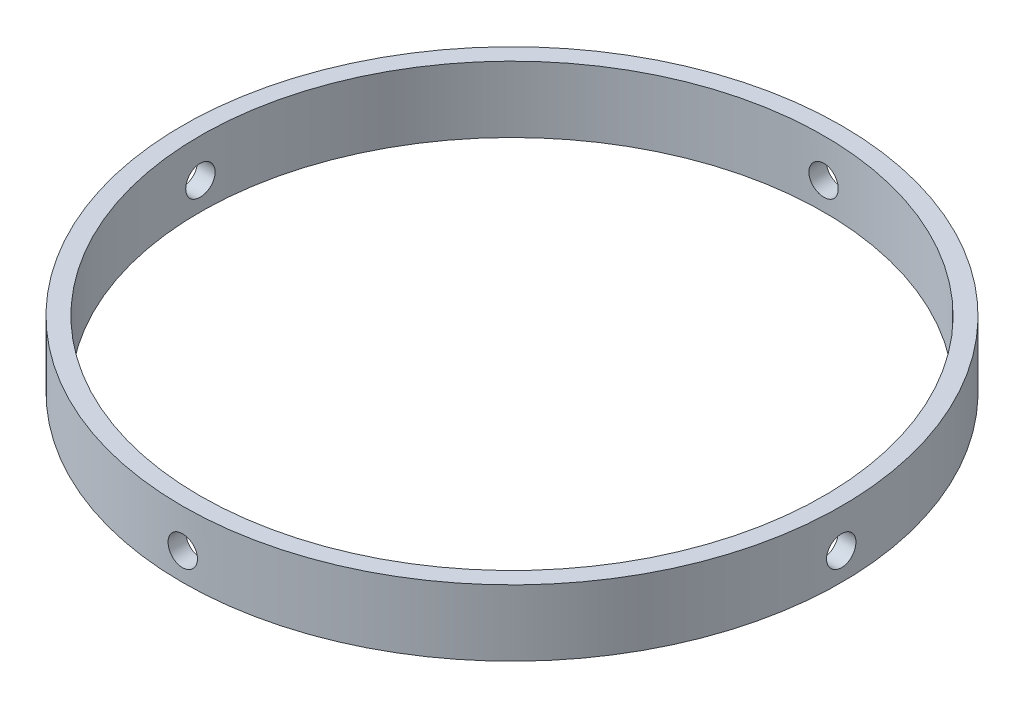
SolidWorks part; units mm, degrees
ref_plane "Front Plane" through (0, 0, 0) normal (0, 0, 1) x (1, 0, 0)
ref_plane "Top Plane" through (0, 0, 0) normal (0, 1, 0) x (1, 0, 0)
ref_plane "Right Plane" through (0, 0, 0) normal (1, 0, 0) x (0, 0, -1)
sketch "Sketch1" plane through (0, 0, 0) normal (0, 1, 0) x (1, 0, 0)
  circle A4 centre (0, 0) radius 35.941
  circle A5 centre (0, 0) radius 37.973
extrude "Boss-Extrude1" add sketch "Sketch1" along normal blind 7.62
sketch "Sketch2" plane through (0, 0, 0) normal (0, 0, 1) x (1, 0, 0)
  circle A0 centre (0, 3.171) radius 1.6929
extrude "Cut-Extrude1" cut sketch "Sketch2" along normal blind 86.62
pattern_circular "CirPattern1" count 4 over 360 of "Cut-Extrude1"
